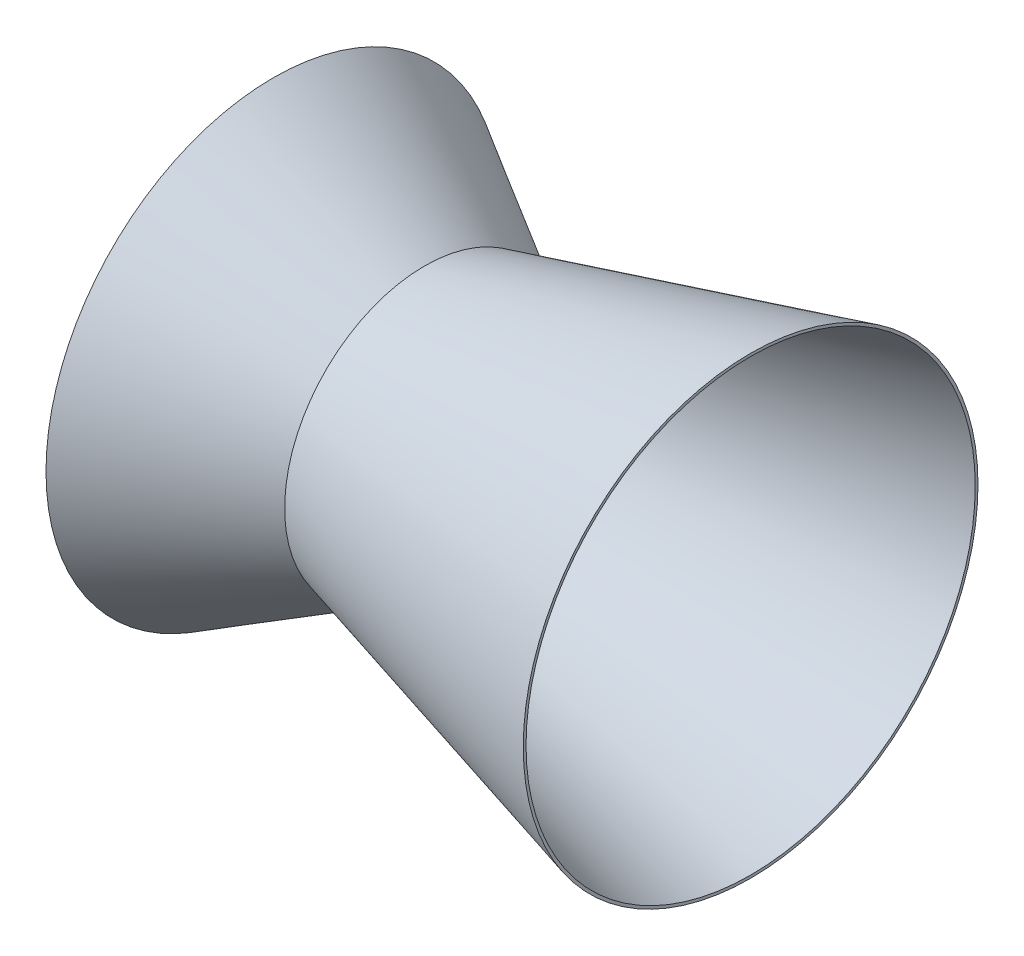
SolidWorks part; units mm, degrees
ref_plane "Front Plane" through (0, 0, 0) normal (0, 0, 1) x (1, 0, 0)
ref_plane "Top Plane" through (0, 0, 0) normal (0, 1, 0) x (1, 0, 0)
ref_plane "Right Plane" through (0, 0, 0) normal (1, 0, 0) x (0, 0, -1)
sketch "Sketch2" plane through (0, 0, 0) normal (0, 0, 1) x (1, 0, 0)
  line L0 (0, 0) -> (0, 85)
  line L1 (0, 85) -> (56.558, 52.346)
  line L2 (56.558, 52.346) -> (178.42, 85)
  line L3 (178.42, 85) -> (178.42, 0)
  line L4 (178.42, 0) -> (0, 0)
  dimension "D1" = 52.346
  dimension "D2" = 85
  dimension "D3" = 178.42
  dimension "D4" = 56.558
  dimension "D5" = 121.862
revolve "Revolve1" add sketch "Sketch2" angle 360 about L4
shell "Shell2" thickness 1
